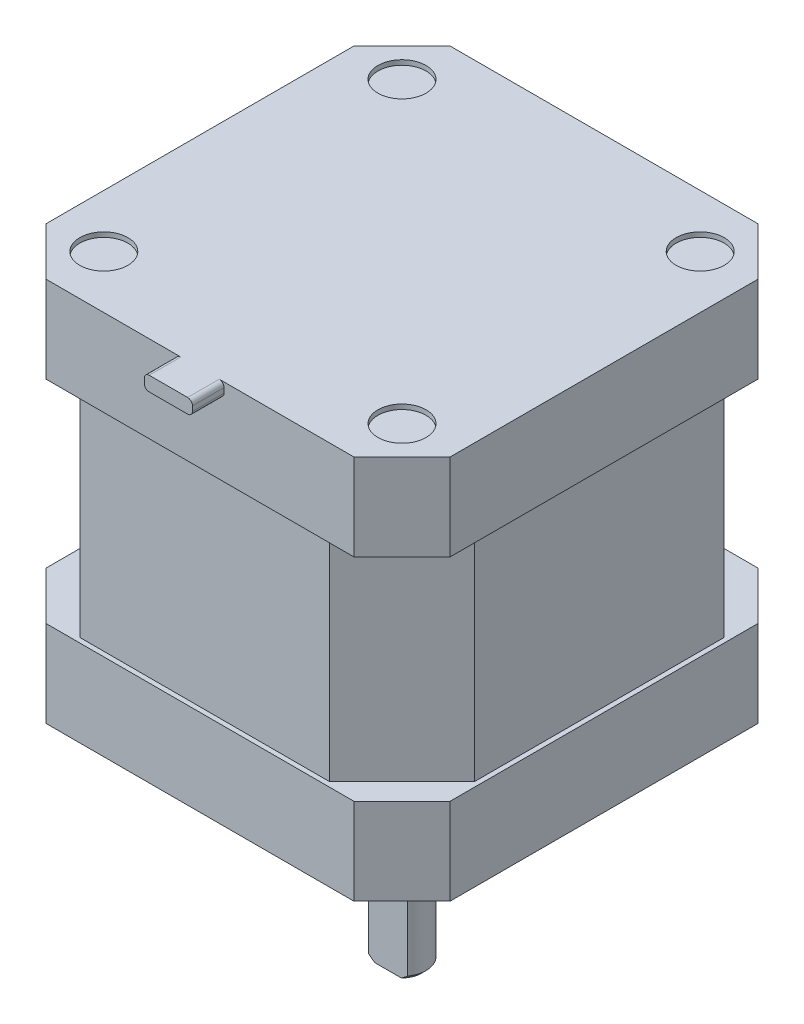
SolidWorks part; units mm, degrees
material "3.0205 (EN-AW 1200)"
ref_plane "Plan de face" through (0, 0, 0) normal (0, 0, 1) x (1, 0, 0)
ref_plane "Plan de dessus" through (0, 0, 0) normal (0, 1, 0) x (1, 0, 0)
ref_plane "Plan de droite" through (0, 0, 0) normal (1, 0, 0) x (0, 0, -1)
ref_plane "Plan1" through (0, 0, 21) normal (0, 0, 1) x (1, 0, 0)
sketch "Esquisse1" plane through (0, 0, 21) normal (0, 0, 1) x (1, 0, 0)
  line L0 (21, 9) -> (-21, 9)
  line L1 (-21, 9) -> (-21, 0)
  line L2 (-21, 0) -> (21, 0)
  line L3 (21, 0) -> (21, 9)
extrude "Boss.-Extru.1" add sketch "Esquisse1" against normal blind 0.5
sketch "Esquisse2" plane through (0, 0, 20.5) normal (0, 0, -1) x (-1, 0, 0)
  line L0 (-20.5, 9) -> (-20.5, 31)
  line L1 (-20.5, 31) -> (20.5, 31)
  line L2 (20.5, 31) -> (20.5, 9)
  line L3 (20.5, 9) -> (21, 9)
  line L4 (21, 9) -> (21, 0)
  line L5 (21, 0) -> (-21, 0)
  line L6 (-21, 0) -> (-21, 9)
  line L7 (-21, 9) -> (-20.5, 9)
extrude "Boss.-Extru.2" add sketch "Esquisse2" along normal blind 41
sketch "Esquisse3" plane through (0, 0, -20.5) normal (0, 0, -1) x (-1, 0, 0)
  line L0 (-21, 9) -> (21, 9)
  line L1 (21, 9) -> (21, 0)
  line L2 (21, 0) -> (-21, 0)
  line L3 (-21, 0) -> (-21, 9)
extrude "Boss.-Extru.3" add sketch "Esquisse3" along normal blind 0.5
ref_plane "Plan2" through (0, 31, 0) normal (0, -1, 0) x (1, 0, 0)
sketch "Esquisse4" plane through (0, 31, 0) normal (0, -1, 0) x (1, 0, 0)
  line L0 (-21, 21) -> (-21, -21)
  line L1 (-21, -21) -> (21, -21)
  line L2 (21, -21) -> (21, 21)
  line L3 (21, 21) -> (-21, 21)
extrude "Boss.-Extru.4" add sketch "Esquisse4" against normal blind 9
sketch "Esquisse5" plane through (0, 0, 21) normal (0, 0, 1) x (1, 0, 0)
  line L0 (-2.5, 40) -> (2.5, 40)
  line L1 (2.5, 40) -> (2.5, 38.5)
  line L2 (2.5, 38.5) -> (-2.5, 38.5)
  line L3 (-2.5, 38.5) -> (-2.5, 40)
extrude "Boss.-Extru.5" add sketch "Esquisse5" along normal blind 3.2869
sketch "Esquisse6" plane through (0, 0, 0) normal (0, -1, 0) x (1, 0, 0)
  circle A0 centre (0, 0) radius 11
extrude "Boss.-Extru.6" add sketch "Esquisse6" along normal blind 2
hole_wizard "Diamètre du perçage Ø15.0 (15)1" positions "Esquisse8" profile "Esquisse7" hole size "Ø15.0" standard "Ansi Metric"
sketch "Esquisse8" plane through (0, -2, 0) normal (0, -1, 0) x (-1, 0, 0)
  point P0 (0, 0)
sketch "Esquisse7" plane through (0, -2, 0) normal (1, 0, 0) x (0, 0, -1)
  line L0 (0, 0) -> (0, 2)
  line L1 (0, 2) -> (7.5, 2)
  line L2 (7.5, 2) -> (7.5, 0)
  line L5 (7.5, 0) -> (0, 0)
  line L10 (0, 2) -> (-7.5, 2) construction
  line L11 (0, -6.35) -> (0, 107.95) construction
  dimension "Diamètre du perçage" = 15
  dimension "Profondeur du perçage" = 2
  dimension "Angle de pointe" = 180
sketch "Esquisse9" plane through (0, 0, 0) normal (0, -1, 0) x (1, 0, 0)
  circle A0 centre (0, 0) radius 2.5
extrude "Boss.-Extru.7" add sketch "Esquisse9" along normal blind 24
sketch "Esquisse10" plane through (0, -24, 0) normal (0, -1, 0) x (1, 0, 0)
  line L0 (-2.0386, 1.447) -> (2.0386, 1.447)
  arc A0 (2.0386, 1.447) -> (-2.0386, 1.447) centre (0, 0) ccw
extrude "Enlèv. mat.-Extru.1" cut sketch "Esquisse10" against normal blind 20
hole_wizard "Diamètre du perçage Ø5.0 (5)1" positions "Esquisse12" profile "Esquisse11" hole size "Ø5.0" standard "Ansi Metric"
sketch "Esquisse12" plane through (0, 40, 0) normal (0, 1, 0) x (1, 0, 0)
  point P0 (15.5, -15.5)
  point P1 (-15.5, -15.5)
  point P2 (-15.5, 15.5)
  point P3 (15.5, 15.5)
sketch "Esquisse11" plane through (15.5, 40, 15.5) normal (1, 0, 0) x (0, 0, 1)
  line L0 (0, 0) -> (0, 0.5)
  line L1 (0, 0.5) -> (2.5, 0.5)
  line L2 (2.5, 0.5) -> (2.5, 0)
  line L5 (2.5, 0) -> (0, 0)
  line L10 (0, 0.5) -> (-2.5, 0.5) construction
  line L11 (0, -6.35) -> (0, 107.95) construction
  dimension "Diamètre du perçage" = 5
  dimension "Profondeur du perçage" = 0.5
  dimension "Angle de pointe" = 180
hole_wizard "Dégagement M21" positions "Esquisse14" profile "Esquisse13" hole size "M2" standard "Ansi Metric"
sketch "Esquisse14" plane through (0, 0, 0) normal (0, -1, 0) x (-1, 0, 0)
  point P0 (15.5, -15.5)
  point P1 (-15.5, -15.5)
  point P2 (-15.5, 15.5)
  point P3 (15.5, 15.5)
sketch "Esquisse13" plane through (-15.5, 0, 15.5) normal (1, 0, 0) x (0, 0, -1)
  line L0 (0, 0) -> (0, 4.5)
  line L1 (0, 4.5) -> (1.2295, 4.5)
  line L2 (1.2295, 4.5) -> (1.2295, 0)
  line L5 (1.2295, 0) -> (0, 0)
  line L10 (0, 4.5) -> (-1.2295, 4.5) construction
  line L11 (0, -6.35) -> (0, 107.95) construction
  dimension "Diamètre du perçage" = 2.459
  dimension "Profondeur du perçage" = 4.5
  dimension "Angle de pointe" = 180
chamfer "Chanfrein1" distance 7.5355 angle 45 4 edges at (-20.5, 20, -20.5) (20.5, 20, -20.5) (20.5, 20, 20.5) (-20.5, 20, 20.5)
chamfer "Chanfrein2" distance 5 angle 45 8 edges at (-21, 35.5, -21) (-21, 4.5, 21) (21, 4.5, -21) (21, 35.5, -21) (-21, 35.5, 21) (21, 4.5, 21) (-21, 4.5, -21) (21, 35.5, 21)
chamfer "Chanfrein3" distance 0.5 angle 45 1 edges at (0, -24, -2.5)
fillet "Congé1" radius 0.5 4 edges at (2.5, 38.5, 22.6435) (-2.5, 38.5, 22.6435) (2.5, 40, 22.6435) (-2.5, 40, 22.6435)
